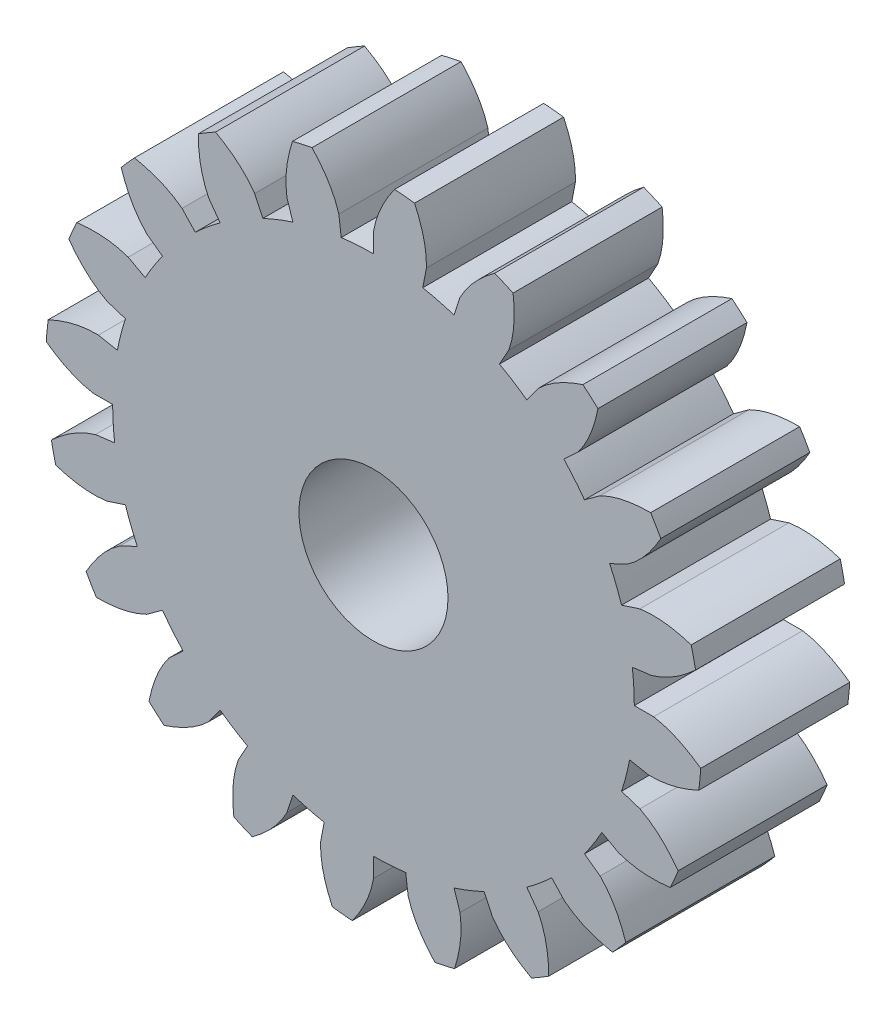
SolidWorks part; units mm, degrees
ref_plane "Front Plane" through (0, 0, 0) normal (0, 0, 1) x (1, 0, 0)
ref_plane "Top Plane" through (0, 0, 0) normal (0, 1, 0) x (1, 0, 0)
ref_plane "Right Plane" through (0, 0, 0) normal (1, 0, 0) x (0, 0, -1)
sketch "Sketch1" plane through (0, 0, 0) normal (0, 0, 1) x (1, 0, 0)
  line L0 (0, 18.794) -> (6.1917, 17.7448) construction
  line L1 (6.1917, 17.7448) -> (11.6921, 14.7142) construction
  line L2 (11.6921, 14.7142) -> (15.887, 10.0408) construction
  line L3 (15.887, 10.0408) -> (18.308, 4.2462) construction
  line L4 (6.1917, 17.7448) -> (0.2623, 19.8137) construction
  line L5 (11.6921, 14.7142) -> (1.8586, 22.5281) construction
  line L6 (15.887, 10.0408) -> (5.8217, 25.9667) construction
  line L7 (18.308, 4.2462) -> (12.6326, 28.7167) construction
  line L8 (0.3296, 19.9973) -> (3.4554, 19.6992) construction
  line L9 (0, 0) -> (1.8925, 19.8483) construction
  line L10 (0, 18.794) -> (0, 0)
  line L11 (0, 0) -> (3.5517, 18.4553)
  circle A0 centre (0, 0) radius 17.5
  circle A1 centre (0, 0) radius 22
  circle A2 centre (0, 0) radius 20 construction
  circle A3 centre (0, 0) radius 18.794 construction
  circle A4 centre (0, 0) radius 5
  spline S0 degree 3 poles (0, 18.794) (0.2289, 20.1881) (3.1768, 25.1592) (8.5939, 27.773) (12.6326, 28.7167) knots 0 0 0 0 0.250202 1 1 1 1
  spline S1 degree 3 poles (3.5517, 18.4553) (3.5904, 19.8675) (1.635, 25.3062) (-3.1905, 28.8966) (-6.978, 30.5865) knots 0 0 0 0 0.250202 1 1 1 1
  dimension "D1" = 44
  dimension "D2" = 35
  dimension "D3" = 37.588
  dimension "D4" = 40
  dimension "D5" = 6.28
  dimension "D10" = 10
  dimension "D6" = 6.28
  dimension "D7" = 12.56
  dimension "D8" = 18.84
  dimension "D9" = 25.12
extrude "Boss-Extrude1" add sketch "Sketch1" along normal blind 10 contours A4 L10 A0 L11 | A4 L11 A0 L10 | L11 S1 A1 S0 L10 A0
pattern_circular "CirPattern1" count 20 over 360 of "Boss-Extrude1"
